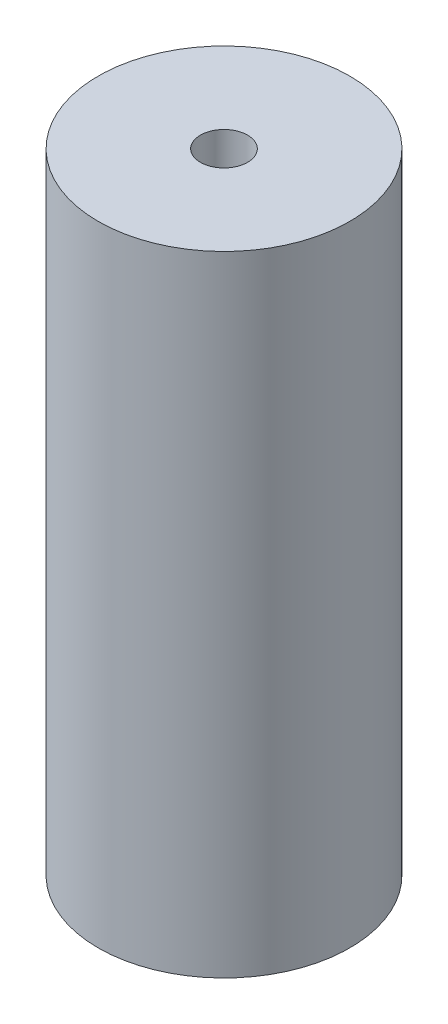
SolidWorks part; units mm, degrees
material "PTFE"
ref_plane "Front Plane" through (0, 0, 0) normal (0, 0, 1) x (1, 0, 0)
ref_plane "Top Plane" through (0, 0, 0) normal (0, 1, 0) x (1, 0, 0)
ref_plane "Right Plane" through (0, 0, 0) normal (1, 0, 0) x (0, 0, -1)
sketch "Sketch1" plane through (0, 0, 0) normal (0, 1, 0) x (1, 0, 0)
  circle A0 centre (0, 0) radius 8
  dimension "D1" = 16
extrude "Boss-Extrude1" add sketch "Sketch1" along normal blind 40
sketch "Sketch2" plane through (0, 40, 0) normal (0, 1, 0) x (1, 0, 0)
  circle A0 centre (0, 0) radius 1.5
  dimension "D1" = 3
extrude "Cut-Extrude1" cut sketch "Sketch2" against normal through all
